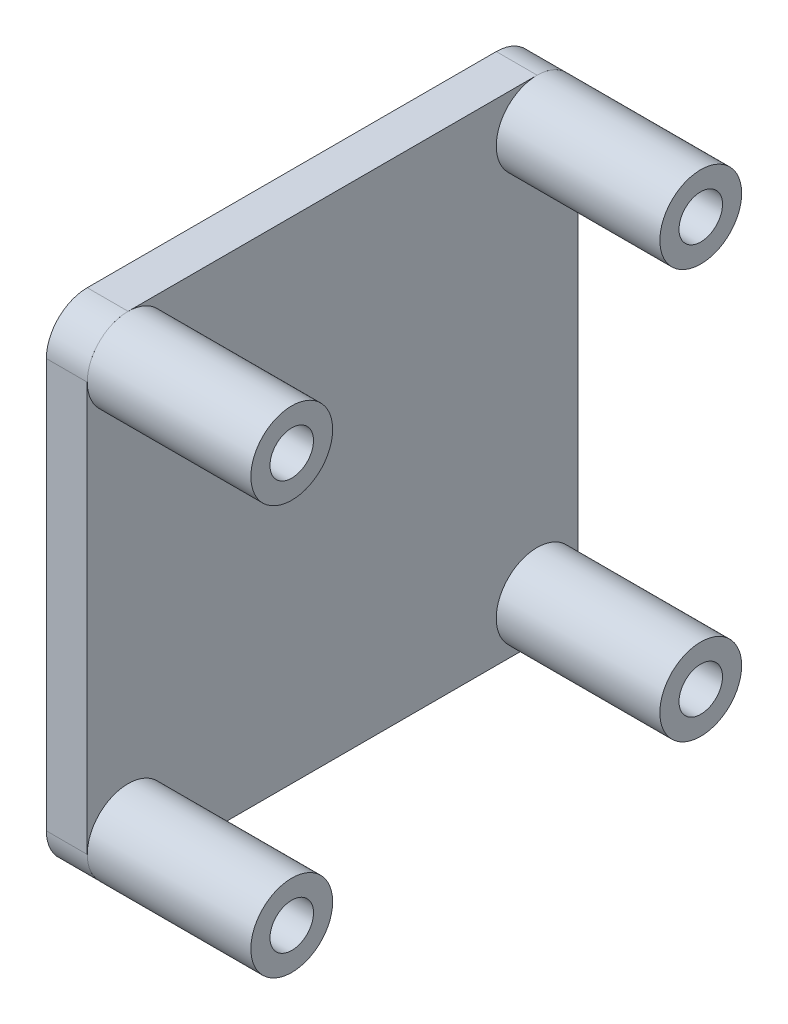
SolidWorks part; units mm, degrees
material "6061-T6 (SS)"
ref_plane "Front Plane" through (0, 0, 0) normal (0, 0, 1) x (1, 0, 0)
ref_plane "Top Plane" through (0, 0, 0) normal (0, 1, 0) x (1, 0, 0)
ref_plane "Right Plane" through (0, 0, 0) normal (1, 0, 0) x (0, 0, -1)
sketch "Sketch1" plane through (0, 0, 0) normal (1, 0, 0) x (0, 0, -1)
  line L1 (38.1, -38.1) -> (-38.1, -38.1)
  line L2 (38.1, -38.1) -> (38.1, 38.1)
  line L3 (38.1, 38.1) -> (-38.1, 38.1)
  line L4 (-38.1, -38.1) -> (-38.1, 38.1)
  line L5 (38.1, -38.1) -> (-38.1, 38.1) construction
  line L6 (38.1, 38.1) -> (-38.1, -38.1) construction
  point P0 (0, 0)
  dimension "D1" = 76.2
  dimension "D2" = 76.2
extrude "Boss-Extrude1" add sketch "Sketch1" along normal blind 6.35
fillet "Fillet1" radius 6.35 4 edges at (3.175, -38.1, -38.1) (3.175, 38.1, -38.1) (3.175, -38.1, 38.1) (3.175, 38.1, 38.1)
sketch "Sketch3" plane through (6.35, 0, 0) normal (1, 0, 0) x (0, 0, -1)
  circle A0 centre (31.75, 31.75) radius 6.35
  circle A1 centre (31.75, -31.75) radius 6.35
  circle A2 centre (-31.75, -31.75) radius 6.35
  circle A3 centre (-31.75, 31.75) radius 6.35
extrude "Boss-Extrude2" add sketch "Sketch3" along normal blind 25.4 separate body
hole_wizard "H (0.266) Diameter Hole1" positions "Sketch5" profile "Sketch4" hole size "H" standard "Ansi Inch" end condition through all
sketch "Sketch5" plane through (31.75, 0, 0) normal (1, 0, 0) x (0, 0, -1)
  point P1 (31.75, 31.75)
  point P4 (-31.75, -31.75)
  point P12 (-31.75, 31.75)
  point P16 (31.75, -31.75)
sketch "Sketch4" plane through (31.75, 31.75, -31.75) normal (0, 1, 0) x (0, 0, -1)
  line L0 (0, 0) -> (0, 31.75)
  line L1 (0, 31.75) -> (3.3782, 31.75)
  line L2 (3.3782, 31.75) -> (3.3782, 0)
  line L5 (3.3782, 0) -> (0, 0)
  line L11 (0, -6.35) -> (0, 107.95) construction
  dimension "Thru Hole Dia." = 6.7564
  dimension "Thru Hole Depth" = 31.75
